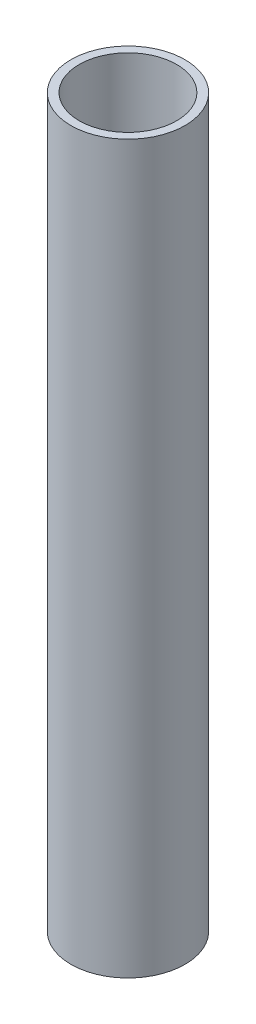
SolidWorks part; units mm, degrees
ref_plane "Front Plane" through (0, 0, 0) normal (0, 0, 1) x (1, 0, 0)
ref_plane "Top Plane" through (0, 0, 0) normal (0, 1, 0) x (1, 0, 0)
ref_plane "Right Plane" through (0, 0, 0) normal (1, 0, 0) x (0, 0, -1)
sketch "Sketch1" plane through (0, 0, 0) normal (0, 1, 0) x (1, 0, 0)
  circle A0 centre (0, 0) radius 27.5
  circle A1 centre (0, 0) radius 23.5
  dimension "D1" = 55
  dimension "D2" = 4
extrude "Boss-Extrude1" add sketch "Sketch1" along normal mid plane 350
